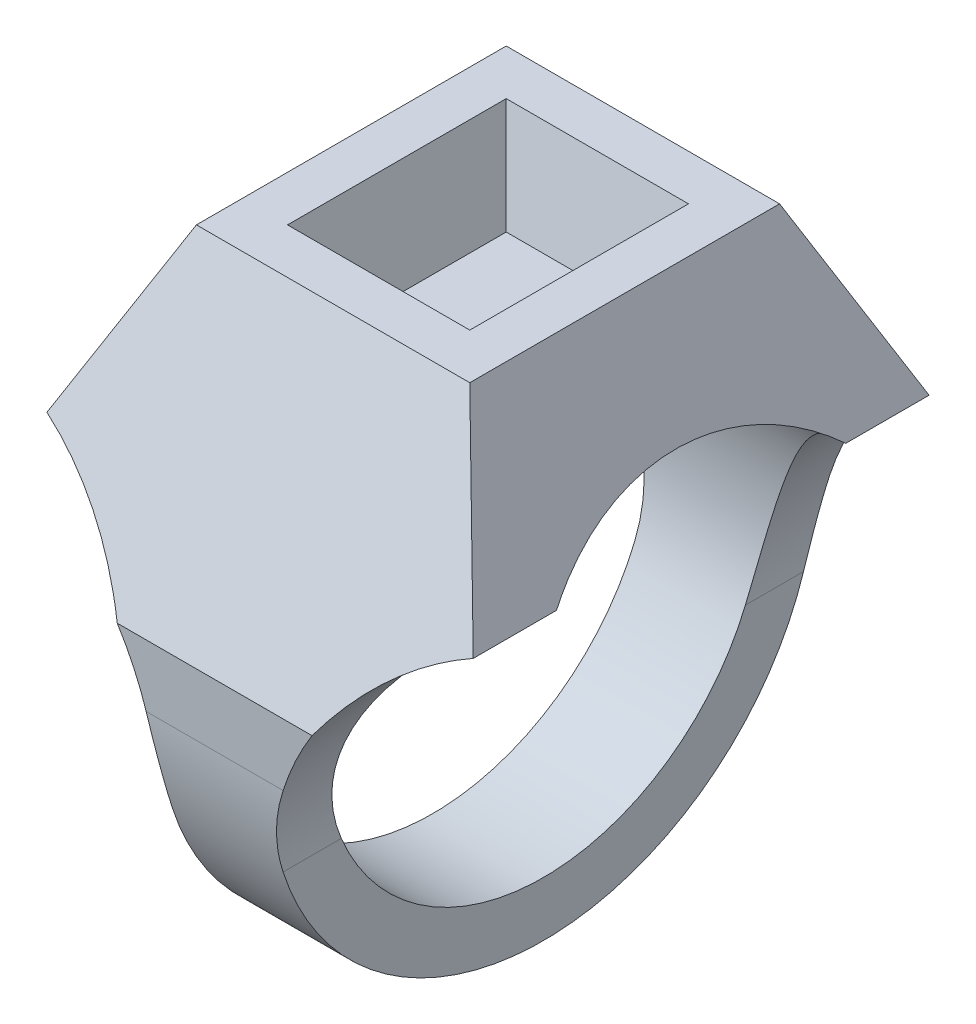
SolidWorks part; units mm, degrees
ref_plane "前视基准面" through (0, 0, 0) normal (0, 0, 1) x (1, 0, 0)
ref_plane "上视基准面" through (0, 0, 0) normal (0, 1, 0) x (1, 0, 0)
ref_plane "右视基准面" through (0, 0, 0) normal (1, 0, 0) x (0, 0, -1)
other "Configuration Table"
sketch "草图1" plane through (0, 0, 0) normal (1, 0, 0) x (0, 0, -1)
  line L0 (-8.5, 18) -> (8.5, 18)
  line L1 (0, 0) -> (0, 22.817) construction
  line L2 (-8.5, 18) -> (-15, 3.4008)
  line L3 (-15, 0) -> (-15, 3.4008)
  line L4 (8.5, 18) -> (15, 3.4008)
  line L5 (15, 0) -> (15, 3.4008)
  circle A0 centre (0, 0) radius 12
  arc A1 (-15, 0) -> (15, 0) centre (0, 0) ccw
  point P7 (0, 18)
  dimension "D1" = 24
  dimension "D2" = 30
  dimension "D3" = 17
  dimension "D4" = 18
  dimension "D5" = 66
extrude "凸台-拉伸1" add sketch "草图1" along normal mid plane 50
sketch "草图2" plane through (0, 0, 0) normal (0, 0, 1) x (1, 0, 0)
  line L0 (-7.5, 18) -> (7.5, 18)
  line L1 (25, 18) -> (-25, 18) construction
  line L2 (7.5, 18) -> (11.6968, 9)
  line L3 (0, 0) -> (0, 25.8686) construction
  line L4 (11.6968, 9) -> (23.3947, -16.0863) construction
  line L5 (3.036, -4.5946) -> (3.036, -15)
  line L6 (-25, -15) -> (25, -15) construction
  line L7 (-7.5, 18) -> (-11.6968, 9)
  line L8 (-3.036, -4.5946) -> (-3.036, -15)
  line L9 (-3.036, -15) -> (3.036, -15)
  arc A0 (11.6968, 9) -> (3.036, -4.5946) centre (18.036, -4.5946) ccw
  arc A1 (-11.6968, 9) -> (-3.036, -4.5946) centre (-18.036, -4.5946) cw
  point P5 (0, 18)
  dimension "D4" = 15
  dimension "D1" = 15
  dimension "D2" = 65
  dimension "D3" = 9
extrude "切除-拉伸1" cut sketch "草图2" against normal through all both and the other way through all flip side to cut
sketch "草图3" plane through (0, 18, 0) normal (0, 1, 0) x (1, 0, 0)
  line L1 (-5, -6) -> (5, -6)
  line L2 (-5, -6) -> (-5, 6)
  line L3 (-5, 6) -> (5, 6)
  line L4 (5, -6) -> (5, 6)
  line L5 (-5, -6) -> (5, 6) construction
  line L6 (-5, 6) -> (5, -6) construction
  point P0 (0, 0)
  dimension "D1" = 12
  dimension "D2" = 10
extrude "切除-拉伸2" cut sketch "草图3" against normal blind 5 draft 15 and the other way through all
